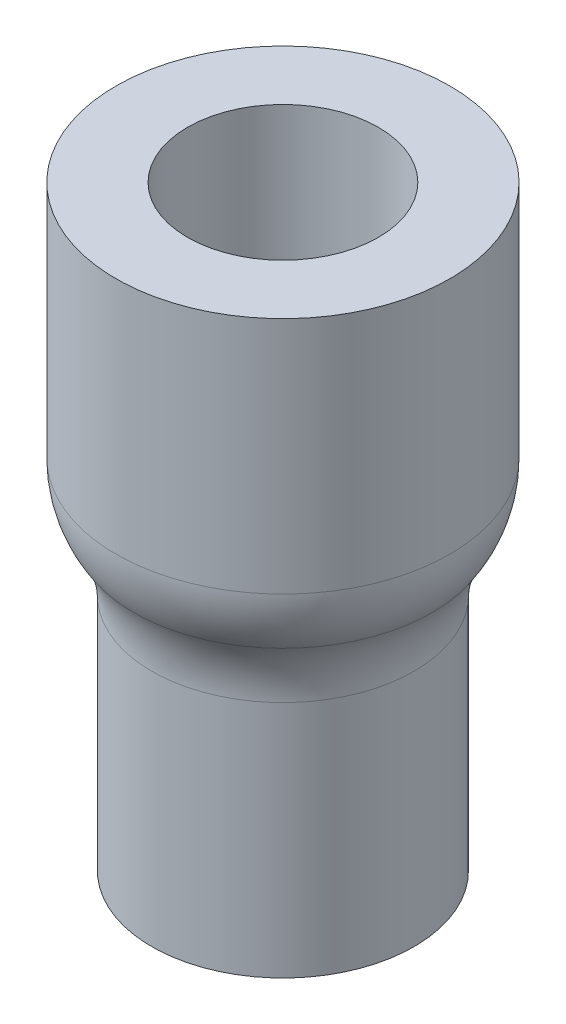
SolidWorks part; units mm, degrees
ref_plane "Front Plane" through (0, 0, 0) normal (0, 0, 1) x (1, 0, 0)
ref_plane "Top Plane" through (0, 0, 0) normal (0, 1, 0) x (1, 0, 0)
ref_plane "Right Plane" through (0, 0, 0) normal (1, 0, 0) x (0, 0, -1)
sketch "Sketch1" plane through (0, 0, 0) normal (0, 0, 1) x (1, 0, 0)
  line L0 (2.5, 0) -> (2.5, 10)
  line L1 (4, 15) -> (4, 25)
  line L2 (4, 25) -> (7, 25)
  line L3 (7, 25) -> (7, 15)
  line L4 (5.5, 10) -> (5.5, 0)
  line L5 (5.5, 0) -> (2.5, 0)
  line L6 (0, 0) -> (0, 25) construction
  arc A0 (2.5, 10) -> (3.25, 12.5) centre (7.0417, 10) cw
  arc A1 (3.25, 12.5) -> (4, 15) centre (-0.5417, 15) ccw
  arc A2 (7, 15) -> (6.25, 12.5) centre (2.4583, 15) cw
  arc A3 (6.25, 12.5) -> (5.5, 10) centre (10.0417, 10) ccw
  dimension "D1" = 5
  dimension "D2" = 8
  dimension "D3" = 14
  dimension "D4" = 10
  dimension "D5" = 25
  dimension "D6" = 11
  dimension "D7" = 10
revolve "Revolve1" add sketch "Sketch1" angle 360 about L6
